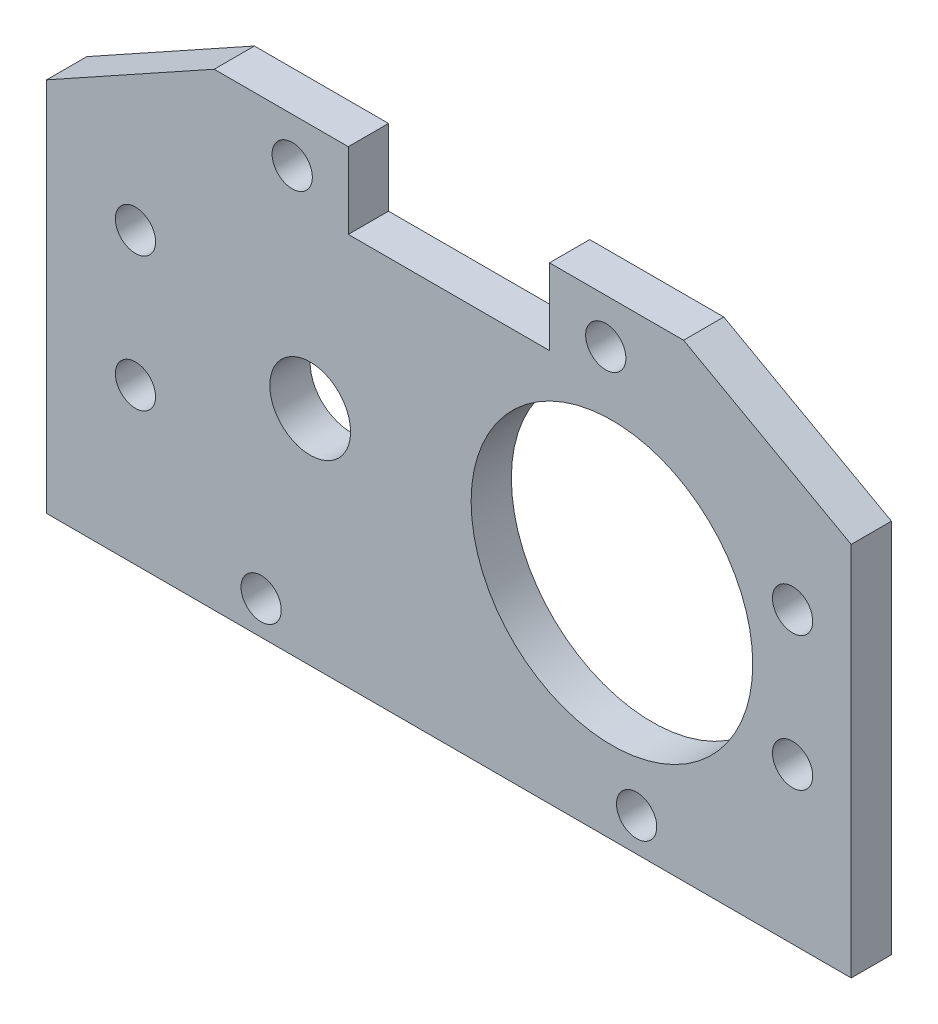
SolidWorks part; units mm, degrees
ref_plane "前视基准面" through (0, 0, 0) normal (0, 0, 1) x (1, 0, 0)
ref_plane "上视基准面" through (0, 0, 0) normal (0, 1, 0) x (1, 0, 0)
ref_plane "右视基准面" through (0, 0, 0) normal (1, 0, 0) x (0, 0, -1)
sketch "草图1" plane through (0, 0, 0) normal (0, 0, 1) x (1, 0, 0)
  line L0 (-7.5, 0) -> (7.5, 0)
  line L1 (7.5, 0) -> (7.5, 5.6658)
  line L2 (7.5, 5.6658) -> (17.5, 5.6658)
  line L3 (17.5, 5.6658) -> (30, -1.2693)
  line L4 (30, -1.2693) -> (30, -29.2693)
  line L5 (30, -29.2693) -> (-30, -29.2693)
  line L6 (0, 0) -> (0, -29.2693) construction
  line L7 (-30, -1.2693) -> (-30, -29.2693)
  line L8 (-7.5, 0) -> (-7.5, 5.6658)
  line L9 (-7.5, 5.6658) -> (-17.5, 5.6658)
  line L10 (-17.5, 5.6658) -> (-30, -1.2693)
  dimension "D1" = 30
  dimension "D2" = 7.5
  dimension "D3" = 10
  dimension "D4" = 28
extrude "凸台-拉伸1" add sketch "草图1" along normal blind 3
sketch "草图2" plane through (0, 0, 0) normal (0, 0, -1) x (-1, 0, 0)
  circle A0 centre (-25.6284, -17.6694) radius 1.5
  circle A1 centre (-25.6284, -7.6694) radius 1.5
  circle A2 centre (23.3716, -17.6694) radius 1.5
  circle A3 centre (23.3716, -7.6694) radius 1.5
  dimension "D1" = 3
  dimension "D2" = 3
  dimension "D3" = 3
  dimension "D4" = 3
extrude "切除-拉伸7" cut sketch "草图2" against normal through all
sketch "草图4" plane through (0, 0, 0) normal (0, 0, -1) x (-1, 0, 0)
  circle A0 centre (-11.6968, 2.3503) radius 1.5
  circle A1 centre (11.6822, 2.3503) radius 1.5
  dimension "D1" = 3
  dimension "D2" = 3
extrude "切除-拉伸8" cut sketch "草图4" against normal through all
sketch "草图6" plane through (0, 0, 0) normal (0, 0, -1) x (-1, 0, 0)
  circle A0 centre (-12.1584, -12.6694) radius 10.5
  circle A1 centre (10.3416, -12.6693) radius 3.01
  dimension "D1" = 21
extrude "切除-拉伸9" cut sketch "草图6" against normal through all
sketch "草图7" plane through (0, 0, 0) normal (0, 0, -1) x (-1, 0, 0)
  line L0 (30, -29.2693) -> (-30, -29.2693) construction
  line L1 (-30, -29.2693) -> (-30, -1.2693) construction
  circle A0 centre (14, -26.7693) radius 1.5
  circle A1 centre (-14, -26.7693) radius 1.5
  dimension "D1" = 3
  dimension "D2" = 3
  dimension "D4" = 16
  dimension "D3" = 2.5
extrude "切除-拉伸10" cut sketch "草图7" against normal through all
